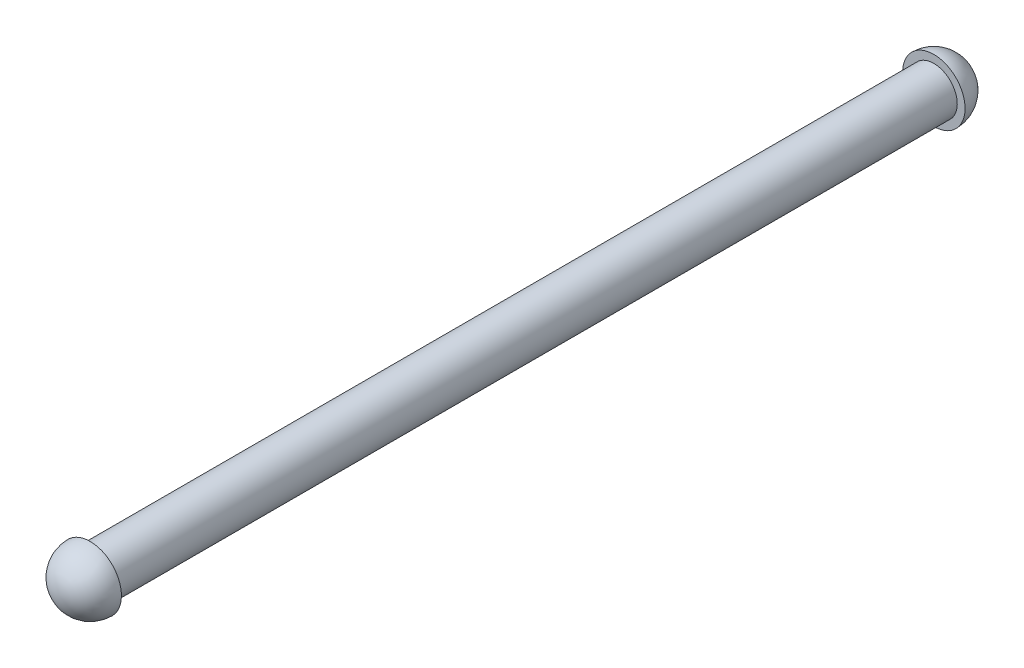
SolidWorks part; units mm, degrees
material "AISI 304"
ref_plane "前视基准面" through (0, 0, 0) normal (0, 0, 1) x (1, 0, 0)
ref_plane "上视基准面" through (0, 0, 0) normal (0, 1, 0) x (1, 0, 0)
ref_plane "右视基准面" through (0, 0, 0) normal (1, 0, 0) x (0, 0, -1)
sketch "草图1" plane through (0, 0, 0) normal (0, 0, 1) x (1, 0, 0)
  line L0 (-0.5, 0) -> (0.5, 0)
  arc A0 (-0.5, 0) -> (0.5, 0) centre (0, 0) ccw
  dimension "D1" = 1
revolve "旋转1" add sketch "草图1" angle 180 about L0
sketch "草图2" plane through (0, 0, 0) normal (0, 0, 1) x (1, 0, 0)
  circle A0 centre (0, 0) radius 0.375
  dimension "D1" = 0.75
extrude "凸台-拉伸1" add sketch "草图2" along normal blind 13.5
sketch "草图3" plane through (0, 0, 13.5) normal (0, 0, 1) x (1, 0, 0)
  line L0 (0, 0.5) -> (0, -0.5)
  arc A0 (0, 0.5) -> (0, -0.5) centre (0, 0) ccw
  dimension "D1" = 1
revolve "旋转2" add sketch "草图3" angle 180 about L0
